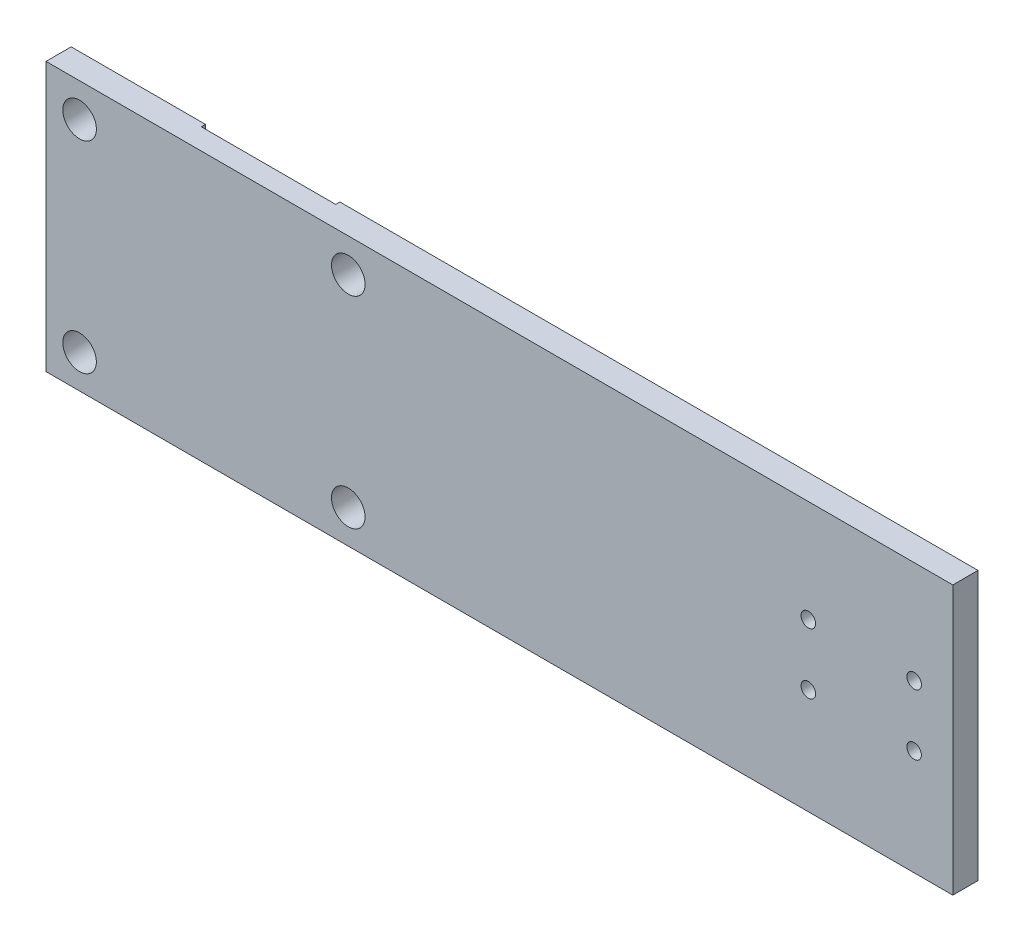
SolidWorks part; units mm, degrees
ref_plane "Front" through (0, 0, 0) normal (0, 0, 1) x (1, 0, 0)
ref_plane "Top" through (0, 0, 0) normal (0, 1, 0) x (1, 0, 0)
ref_plane "Right" through (0, 0, 0) normal (1, 0, 0) x (0, 0, -1)
sketch "Sketch1" plane through (0, 0, 0) normal (0, 0, 1) x (1, 0, 0)
  line L1 (0, 0) -> (342.9, 0)
  line L2 (0, 0) -> (0, 101.6)
  line L3 (0, 101.6) -> (342.9, 101.6)
  line L4 (342.9, 0) -> (342.9, 101.6)
  dimension "D1" = 101.6
  dimension "D2" = 342.9
extrude "Boss-Extrude1" add sketch "Sketch1" along normal blind 9.525
sketch "Sketch2" plane through (0, 0, 0) normal (1, 0, 0) x (0, 0, -1)
  line L0 (0, 0) -> (0, 101.6) construction
  line L1 (0, 76.2) -> (-1.5875, 76.2)
  line L2 (0, 76.2) -> (0, 25.4)
  line L3 (0, 25.4) -> (-1.5875, 25.4)
  line L4 (-1.5875, 76.2) -> (-1.5875, 25.4)
  line L5 (-9.525, 101.6) -> (0, 101.6) construction
  dimension "D1" = 25.4
  dimension "D2" = 50.8
  dimension "D3" = 1.5875
extrude "Cut-Extrude1" cut sketch "Sketch2" against normal blind 9.525 and the other way blind 208.28 from offset 60.325
sketch "Sketch3" plane through (0, 0, 0) normal (0, 0, -1) x (-1, 0, 0)
  line L0 (-342.9, 101.6) -> (0, 101.6) construction
  line L1 (0, 101.6) -> (0, 0) construction
  line L4 (18.8245, 50.8) -> (-106.6282, 50.8) construction
  circle A1 centre (-12.7, 88.9) radius 6.35
  circle A2 centre (-114.3, 88.9) radius 6.35
  circle A3 centre (-114.3, 12.7) radius 6.35
  circle A4 centre (-12.7, 12.7) radius 6.35
  dimension "D1" = 12.7
  dimension "D3" = 12.7
  dimension "D2" = 12.7
  dimension "D4" = 76.2
  dimension "D5" = 101.6
extrude "Cut-Extrude4" cut sketch "Sketch3" against normal through all both
sketch "Sketch5" plane through (0, 0, 0) normal (0, 0, -1) x (-1, 0, 0)
  line L0 (-342.9, 101.6) -> (0, 101.6) construction
  line L1 (-101.6, 101.6) -> (-50.8, 101.6)
  line L2 (-101.6, 101.6) -> (-101.6, 0)
  line L3 (-101.6, 0) -> (-50.8, 0)
  line L4 (-50.8, 101.6) -> (-50.8, 0)
  line L5 (0, 0) -> (-342.9, 0) construction
  line L6 (0, 101.6) -> (0, 0) construction
  dimension "D1" = 50.8
  dimension "D2" = 50.8
extrude "Cut-Extrude5" cut sketch "Sketch5" along direction (0, 0, -1) on the side against the normal up to surface (1.5875 mm away)
hole_wizard "M5 Clearance Hole1" positions "Sketch6" profile "Sketch7" hole size "M5" standard "ANSI Metric" end condition through all
sketch "Sketch6" plane through (0, 0, 9.525) normal (0, 0, 1) x (1, 0, 0)
  line L0 (342.9, 0) -> (342.9, 101.6) construction
  line L1 (0, 0) -> (342.9, 0) construction
  point P0 (328.2696, 62.9412)
  point P2 (328.2696, 39.9288)
  point P4 (288.2646, 39.9288)
  point P6 (288.2646, 62.9412)
  dimension "D1" = 40.005
  dimension "D2" = 14.6304
  dimension "D3" = 39.9288
  dimension "D4" = 23.0124
  dimension "D5" = 14.6304
  dimension "D6" = 40.005
  dimension "D7" = 23.0124
sketch "Sketch7" plane through (328.2696, 62.9412, 9.525) normal (1, 0, 0) x (0, -1, 0)
  line L0 (0, 0) -> (0, 9.525)
  line L1 (0, 9.525) -> (2.75, 9.525)
  line L2 (2.75, 9.525) -> (2.75, 0)
  line L5 (2.75, 0) -> (0, 0)
  line L11 (0, -6.35) -> (0, 107.95) construction
  dimension "Thru Hole Dia." = 5.5
  dimension "Thru Hole Depth" = 9.525
